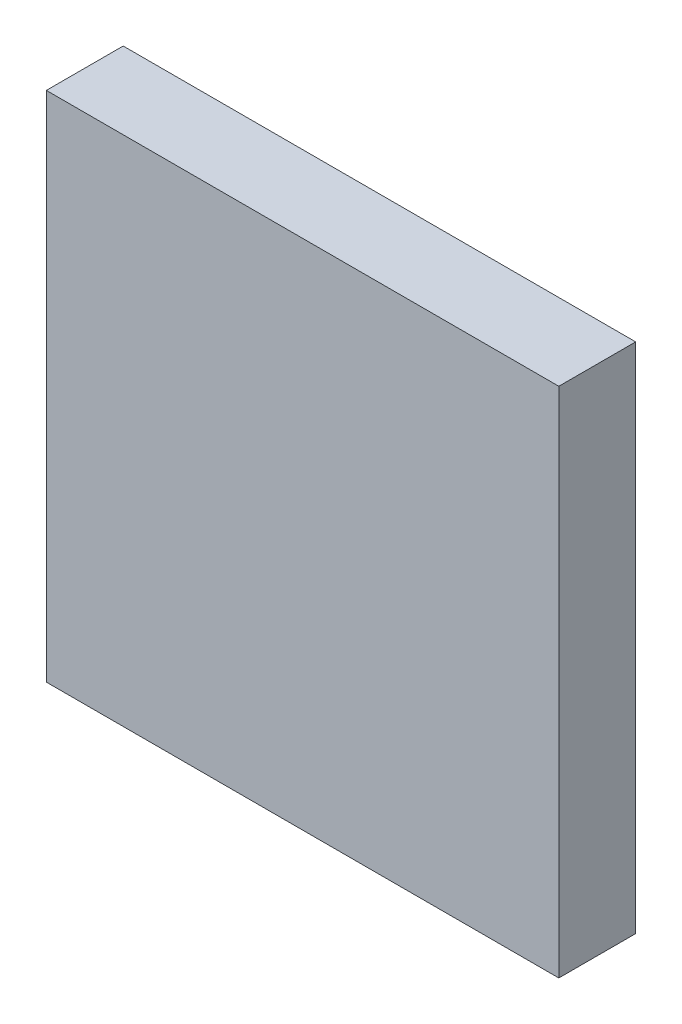
SolidWorks part; units mm, degrees
ref_plane "Alzado" through (0, 0, 0) normal (0, 0, 1) x (1, 0, 0)
ref_plane "Planta" through (0, 0, 0) normal (0, 1, 0) x (1, 0, 0)
ref_plane "Vista lateral" through (0, 0, 0) normal (1, 0, 0) x (0, 0, -1)
sketch "Croquis1" plane through (0, 0, 0) normal (0, 0, 1) x (1, 0, 0)
  line L1 (0, 0) -> (100, 0)
  line L2 (0, 0) -> (0, 100)
  line L3 (0, 100) -> (100, 100)
  line L4 (100, 0) -> (100, 100)
  dimension "D1" = 100
  dimension "D2" = 100
extrude "Saliente-Extruir1" add sketch "Croquis1" along normal blind 15
